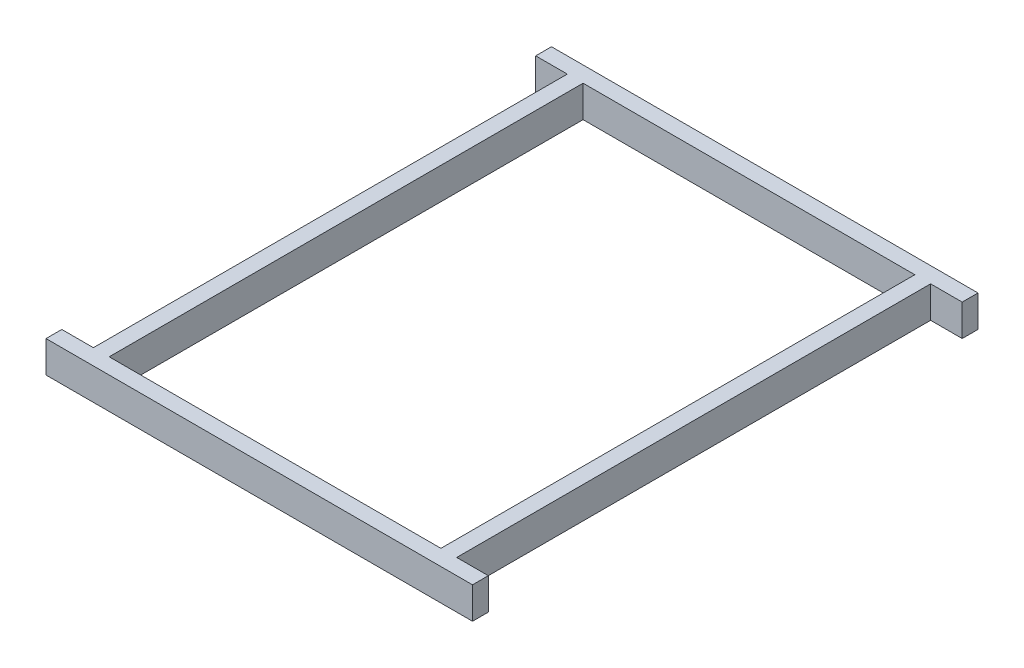
SolidWorks part; units mm, degrees
ref_plane "Front Plane" through (0, 0, 0) normal (0, 0, 1) x (1, 0, 0)
ref_plane "Top Plane" through (0, 0, 0) normal (0, 1, 0) x (1, 0, 0)
ref_plane "Right Plane" through (0, 0, 0) normal (1, 0, 0) x (0, 0, -1)
sketch "Sketch1" plane through (0, 0, 0) normal (0, 1, 0) x (1, 0, 0)
  line L0 (-342.9, 0) -> (342.9, 0)
  line L1 (342.9, 0) -> (342.9, 25.4)
  line L2 (342.9, 25.4) -> (292.1, 25.4)
  line L3 (292.1, 25.4) -> (292.1, 787.4)
  line L4 (292.1, 787.4) -> (342.9, 787.4)
  line L5 (342.9, 787.4) -> (342.9, 812.8)
  line L6 (342.9, 812.8) -> (-342.9, 812.8)
  line L7 (-342.9, 812.8) -> (-342.9, 787.4)
  line L8 (-342.9, 787.4) -> (-292.1, 787.4)
  line L9 (-292.1, 787.4) -> (-292.1, 25.4)
  line L10 (-292.1, 25.4) -> (-342.9, 25.4)
  line L11 (-342.9, 25.4) -> (-342.9, 0)
  line L13 (-266.7, 787.4) -> (266.7, 787.4)
  line L14 (-266.7, 787.4) -> (-266.7, 25.4)
  line L15 (-266.7, 25.4) -> (266.7, 25.4)
  line L16 (266.7, 787.4) -> (266.7, 25.4)
  point P14 (0, 0)
  dimension "D1" = 685.8
  dimension "D2" = 812.8
  dimension "D3" = 25.4
  dimension "D4" = 50.8
  dimension "D5" = 50.8
  dimension "D6" = 25.4
  dimension "D7" = 50.8
  dimension "D8" = 25.4
  dimension "D9" = 25.4
  dimension "D10" = 25.4
  dimension "D11" = 25.4
  dimension "D12" = 25.4
extrude "Boss-Extrude1" add sketch "Sketch1" along normal blind 50.8
